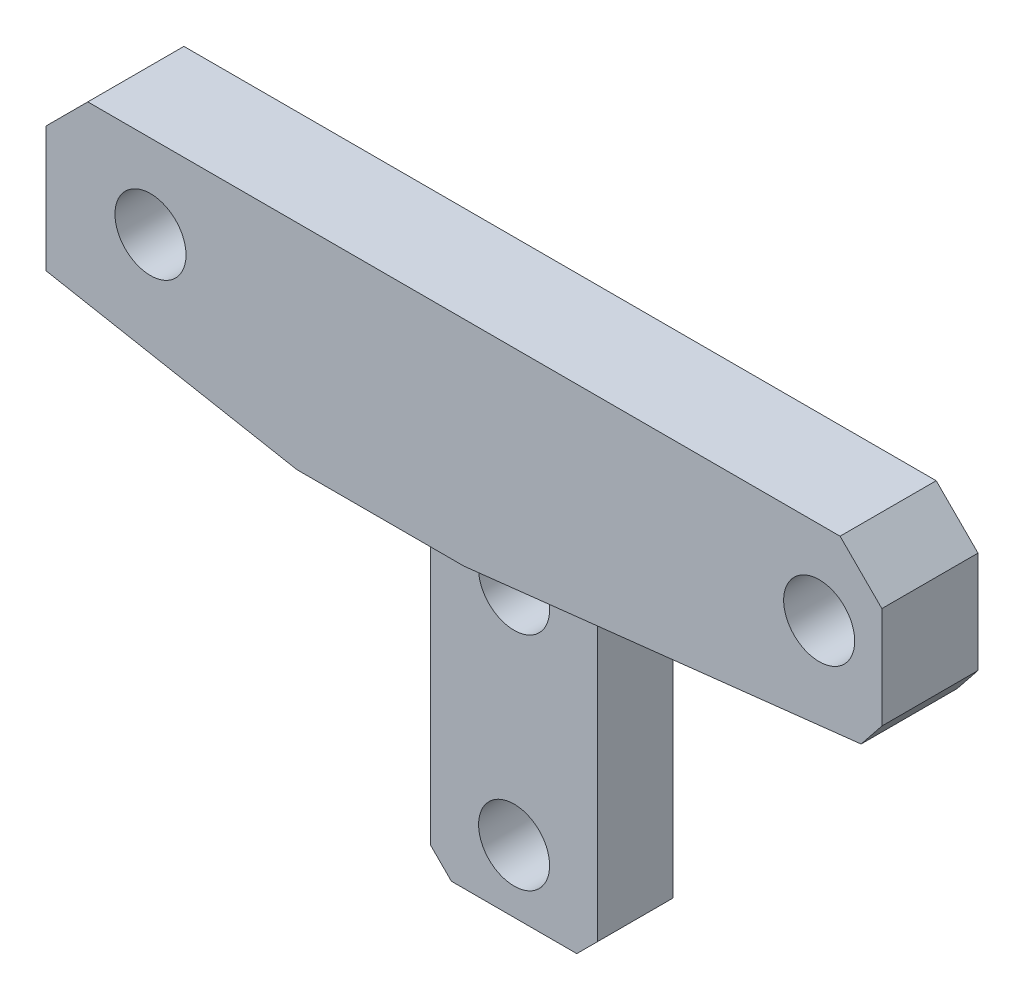
SolidWorks part; units mm, degrees
ref_plane "前视基准面" through (0, 0, 0) normal (0, 0, 1) x (1, 0, 0)
ref_plane "上视基准面" through (0, 0, 0) normal (0, 1, 0) x (1, 0, 0)
ref_plane "右视基准面" through (0, 0, 0) normal (1, 0, 0) x (0, 0, -1)
other "Configuration Table"
sketch "草图1" plane through (0, 0, 0) normal (0, 0, 1) x (1, 0, 0)
  line L1 (-10, 2) -> (10, 2)
  line L2 (-10, 2) -> (-10, -2)
  line L4 (10, 2) -> (10, -2)
  line L5 (-10, 2) -> (10, -2) construction
  line L6 (-10, -2) -> (10, 2) construction
  line L8 (-4, -3.12) -> (-4, -13)
  line L9 (-4, -13) -> (0, -13)
  line L10 (0, -3.12) -> (0, -13)
  line L11 (-10, -2) -> (-4, -3.12)
  line L12 (0, -3.12) -> (10, -2)
  circle A0 centre (-7.5, 0) radius 0.85
  circle A1 centre (8.5, 0) radius 0.85
  circle A2 centre (-2, -11.5) radius 0.85
  circle A3 centre (-2, -6.2) radius 0.85
  point P0 (0, 0)
  dimension "D5" = 1.12
  dimension "D7" = 9.88
  dimension "D12" = 1.12
  dimension "D4" = 1.7
  dimension "D1" = 20
  dimension "D2" = 4
  dimension "D3" = 4
  dimension "D6" = 2.5
  dimension "D8" = 1.5
  dimension "D9" = 10
  dimension "D10" = 2
  dimension "D11" = 2
  dimension "D14" = 2
  dimension "D15" = 2
  dimension "D16" = 1.5
  dimension "D17" = 5.3
extrude "凸台-拉伸2" add sketch "草图1" along normal blind 5.5
sketch "草图3" plane through (0, 0, 5.5) normal (0, 0, -1) x (-1, 0, 0)
  line L0 (0, -3.12) -> (4, -3.12)
  line L8 (-10, 2) -> (-10, -2)
  line L9 (-10, -2) -> (0, -3.12)
  line L10 (0, -3.12) -> (0, -13)
  line L11 (0, -13) -> (4, -13)
  line L12 (4, -13) -> (4, -3.12)
  line L14 (10, -2) -> (10, 2)
  line L15 (10, 2) -> (-10, 2)
  line L18 (0, -3.12) -> (0, -13)
  line L19 (0, -13) -> (4, -13)
  line L20 (4, -13) -> (4, -3.12)
  line L25 (4, -3.12) -> (10, -2)
  circle A0 centre (2, -11.5) radius 0.85 construction
  circle A1 centre (2, -6.2) radius 0.85 construction
  circle A2 centre (2, -11.5) radius 0.85
  circle A3 centre (2, -6.2) radius 0.85
  dimension "D2" = 0
  dimension "D1" = 0
extrude "切除-拉伸2" cut sketch "草图3" along normal blind 3.2
chamfer "倒角1" distance 1 angle 45 1 edges at (-2, -3.12, 2.3)
chamfer "倒角2" distance 1 angle 45 2 edges at (-10, 2, 2.75) (10, 2, 2.75)
chamfer "倒角3" distance 0.5 angle 45 2 edges at (-4, -13, 1.15) (0, -13, 1.15)
sketch "草图4" plane through (0, 0, 0) normal (0, 0, 1) x (1, 0, 0)
  line L6 (-10, -2.5) -> (10, -2.5)
  line L13 (-4, -3.12) -> (0, -3.12)
  line L17 (0, -3.12) -> (10, -2)
  line L18 (10, -2) -> (10, 1)
  line L19 (10, 1) -> (9, 2)
  line L20 (9, 2) -> (-9, 2)
  line L21 (-9, 2) -> (-10, 1)
  line L22 (-10, 1) -> (-10, -2)
  line L23 (-10, -2) -> (-4, -3.12)
  line L30 (10, -2.5) -> (10, 1)
  line L31 (10, 1) -> (9, 2)
  line L32 (9, 2) -> (-9, 2)
  line L33 (-9, 2) -> (-10, 1)
  line L34 (-10, 1) -> (-10, -2.5)
  circle A0 centre (8.5, 0) radius 0.85 construction
  circle A1 centre (-7.5, 0) radius 0.85 construction
  circle A2 centre (8.5, 0) radius 0.85
  circle A3 centre (-7.5, 0) radius 0.85
  dimension "D2" = 4.5
  dimension "D1" = 0
extrude "切除-拉伸3" cut sketch "草图4" along normal blind 3.2
chamfer "倒角4" distance 0.5 angle 45 1 edges at (10, -2, 4.35)
sketch "草图5" plane through (0, 0, 0) normal (0, 0, -1) x (-1, 0, 0)
  line L8 (4, -3.12) -> (7.3214, -2.5)
  line L9 (7.3214, -2.5) -> (-5.5357, -2.5)
  line L10 (-5.5357, -2.5) -> (0, -3.12)
  line L11 (0, -3.12) -> (0, -12.5)
  line L12 (0, -12.5) -> (0.5, -13)
  line L13 (0.5, -13) -> (3.5, -13)
  line L14 (3.5, -13) -> (4, -12.5)
  line L15 (4, -12.5) -> (4, -3.12)
  line L16 (4, -3.12) -> (7.3214, -2.5)
  line L17 (7.3214, -2.5) -> (-5.5357, -2.5)
  line L18 (-5.5357, -2.5) -> (0, -3.12)
  line L19 (0, -3.12) -> (0, -12.5)
  line L20 (0, -12.5) -> (0.5, -13)
  line L21 (0.5, -13) -> (3.5, -13)
  line L22 (3.5, -13) -> (4, -12.5)
  line L23 (4, -12.5) -> (4, -3.12)
  dimension "D1" = 0
extrude "切除-拉伸4" cut sketch "草图5" against normal blind 0.5
